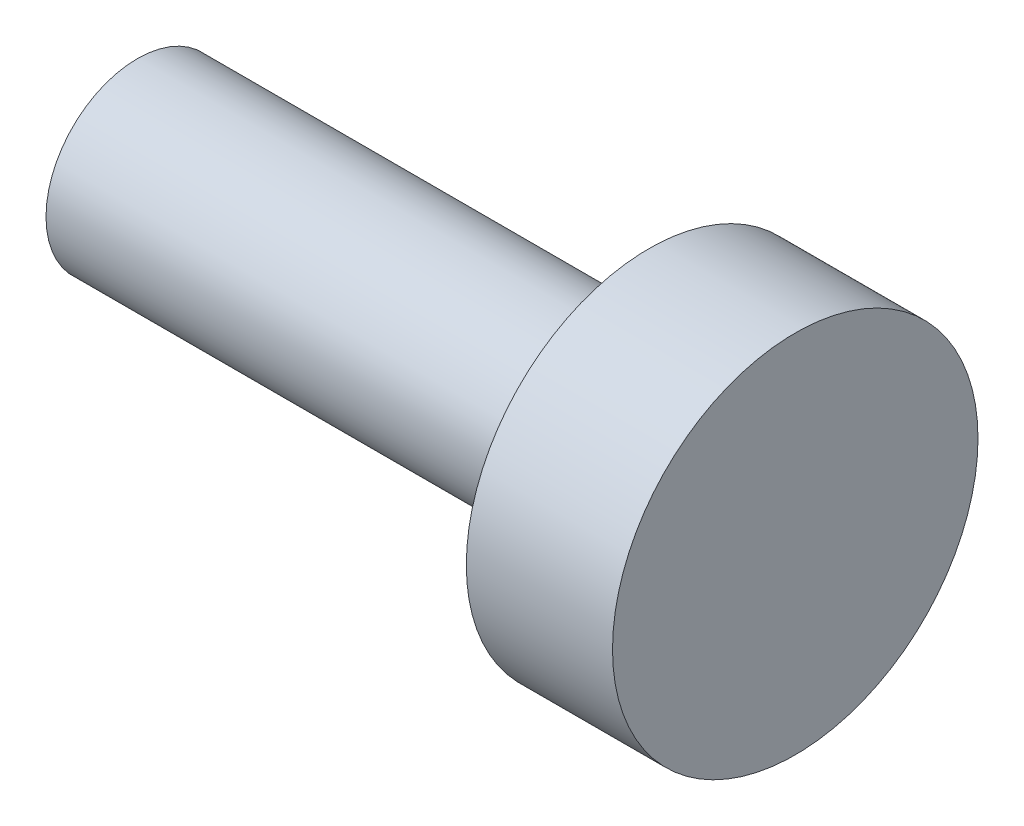
SolidWorks part; units mm, degrees
ref_plane "Front Plane" through (0, 0, 0) normal (0, 0, 1) x (1, 0, 0)
ref_plane "Top Plane" through (0, 0, 0) normal (0, 1, 0) x (1, 0, 0)
ref_plane "Right Plane" through (0, 0, 0) normal (1, 0, 0) x (0, 0, -1)
sketch "Sketch1" plane through (0, 0, 0) normal (0, 0, 1) x (1, 0, 0)
  line L0 (0, 0) -> (22.86, 0)
  line L1 (22.86, 0) -> (22.86, 6.35)
  line L2 (22.86, 6.35) -> (17.78, 6.35)
  line L3 (17.78, 6.35) -> (17.78, 3.175)
  line L4 (17.78, 3.175) -> (0, 3.175)
  line L5 (0, 3.175) -> (0, 0)
  dimension "D1" = 6.35
  dimension "D2" = 3.175
  dimension "D3" = 5.08
  dimension "D4" = 22.86
revolve "Revolve1" add sketch "Sketch1" angle 360 about L0
